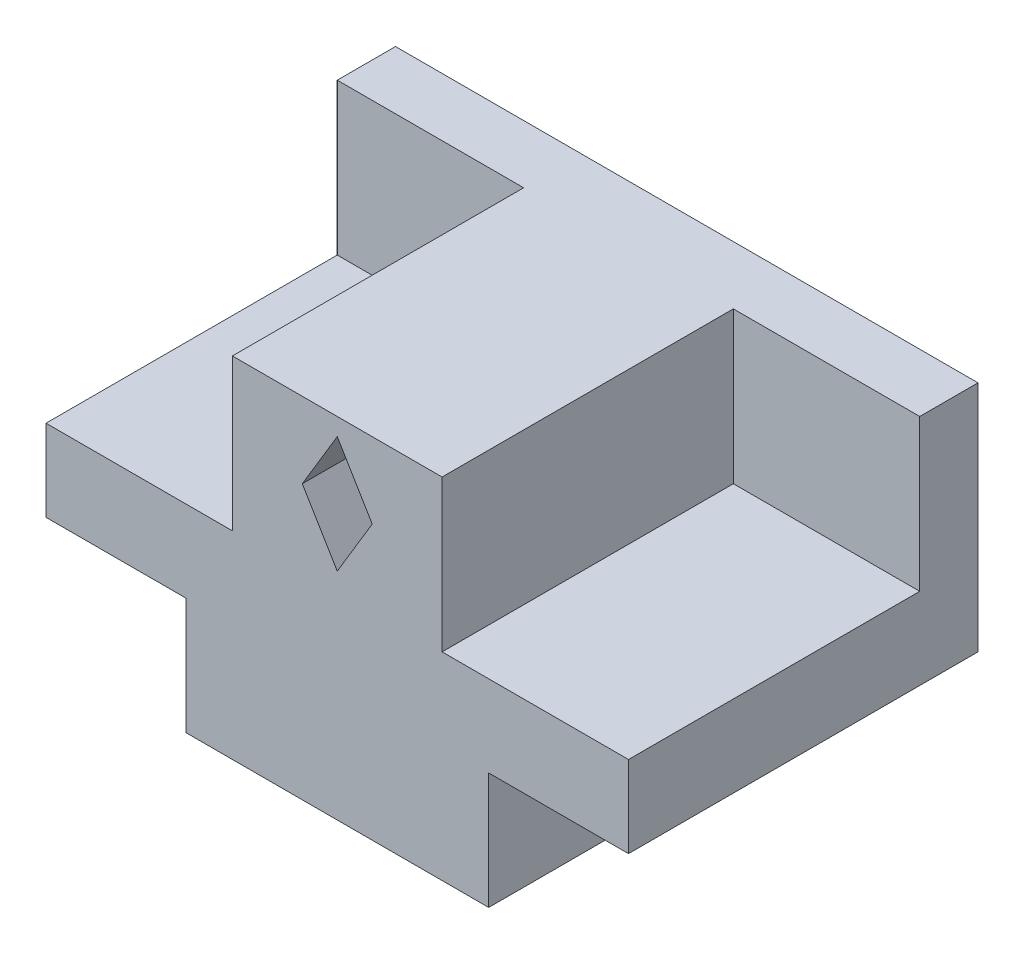
SolidWorks part; units mm, degrees
ref_plane "Спереди" through (0, 0, 0) normal (0, 0, 1) x (1, 0, 0)
ref_plane "Сверху" through (0, 0, 0) normal (0, 1, 0) x (1, 0, 0)
ref_plane "Справа" through (0, 0, 0) normal (1, 0, 0) x (0, 0, -1)
sketch "Эскиз1" plane through (0, 0, 0) normal (0, 0, 1) x (1, 0, 0)
  line L0 (9, 23.5) -> (0, 23.5) construction
  line L1 (0, 0) -> (25, 0)
  line L2 (0, 0) -> (0, 30)
  line L3 (0, 30) -> (25, 30)
  line L4 (25, 0) -> (25, 30)
  line L5 (25, 0) -> (13, 0)
  line L6 (25, 0) -> (25, 10)
  line L7 (25, 10) -> (13, 10)
  line L8 (13, 0) -> (13, 10)
  line L9 (25, 30) -> (9, 30)
  line L10 (25, 30) -> (25, 17)
  line L11 (25, 17) -> (9, 17)
  line L12 (9, 30) -> (9, 17)
  line L13 (0, 28.5) -> (3, 23.5)
  line L14 (3, 23.5) -> (0, 18.5)
  dimension "D1" = 25
  dimension "D2" = 30
  dimension "D3" = 12
  dimension "D4" = 10
  dimension "D5" = 16
  dimension "D6" = 7
  dimension "D7" = 3
  dimension "D8" = 5
extrude "Бобышка-Вытянуть1" add sketch "Эскиз1" along normal blind 30 contours L12 L0 L14 L2 L1 L8 L7 L4 L11 | L0 L12 L3 L2 L13
mirror "Зеркальное отражение1" about plane through (0, 0, 30) normal (-1, 0, 0) of "Бобышка-Вытянуть1"
sketch "Эскиз2" plane through (0, 0, 0) normal (0, 0, -1) x (-1, 0, 0)
  line L0 (9, 30) -> (-9, 30) construction
  line L1 (25, 10) -> (-25, 10)
  line L2 (25, 10) -> (25, 30)
  line L3 (25, 30) -> (-25, 30)
  line L4 (-25, 10) -> (-25, 30)
  line L5 (-25, 10) -> (-25, 17) construction
  line L6 (0, 28.5) -> (3, 23.5) construction
  line L7 (3, 23.5) -> (0, 18.5) construction
  line L8 (-3, 23.5) -> (0, 18.5) construction
  line L9 (0, 28.5) -> (-3, 23.5) construction
  line L10 (0, 28.5) -> (3, 23.5)
  line L11 (3, 23.5) -> (0, 18.5)
  line L12 (-3, 23.5) -> (0, 18.5)
  line L13 (0, 28.5) -> (-3, 23.5)
extrude "Бобышка-Вытянуть2" add sketch "Эскиз2" against normal blind 5
